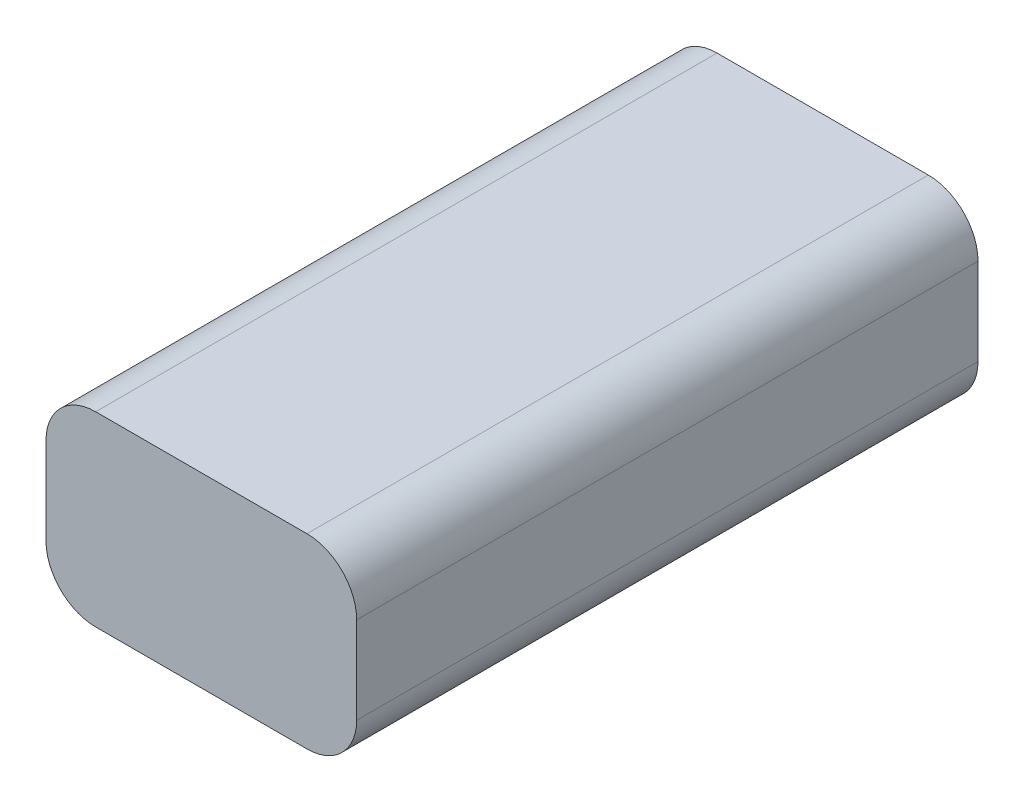
SolidWorks part; units mm, degrees
material "ABS PC"
ref_plane "前视基准面" through (0, 0, 0) normal (0, 0, 1) x (1, 0, 0)
ref_plane "上视基准面" through (0, 0, 0) normal (0, 1, 0) x (1, 0, 0)
ref_plane "右视基准面" through (0, 0, 0) normal (1, 0, 0) x (0, 0, -1)
sketch "草图1" plane through (0, 0, 0) normal (0, 1, 0) x (1, 0, 0)
  line L1 (-25, 50) -> (25, 50)
  line L2 (-25, 50) -> (-25, -50)
  line L3 (-25, -50) -> (25, -50)
  line L4 (25, 50) -> (25, -50)
  line L5 (-25, 50) -> (25, -50) construction
  line L6 (-25, -50) -> (25, 50) construction
  point P0 (0, 0)
  dimension "D1" = 100
  dimension "D2" = 50
extrude "凸台-拉伸1" add sketch "草图1" along normal blind 30
fillet "圆角1" radius 8 4 edges at (-25, 0, 0) (25, 0, 0) (25, 30, 0) (-25, 30, 0)
sketch "草图2" plane through (0, 30, 0) normal (0, 1, 0) x (1, 0, 0)
